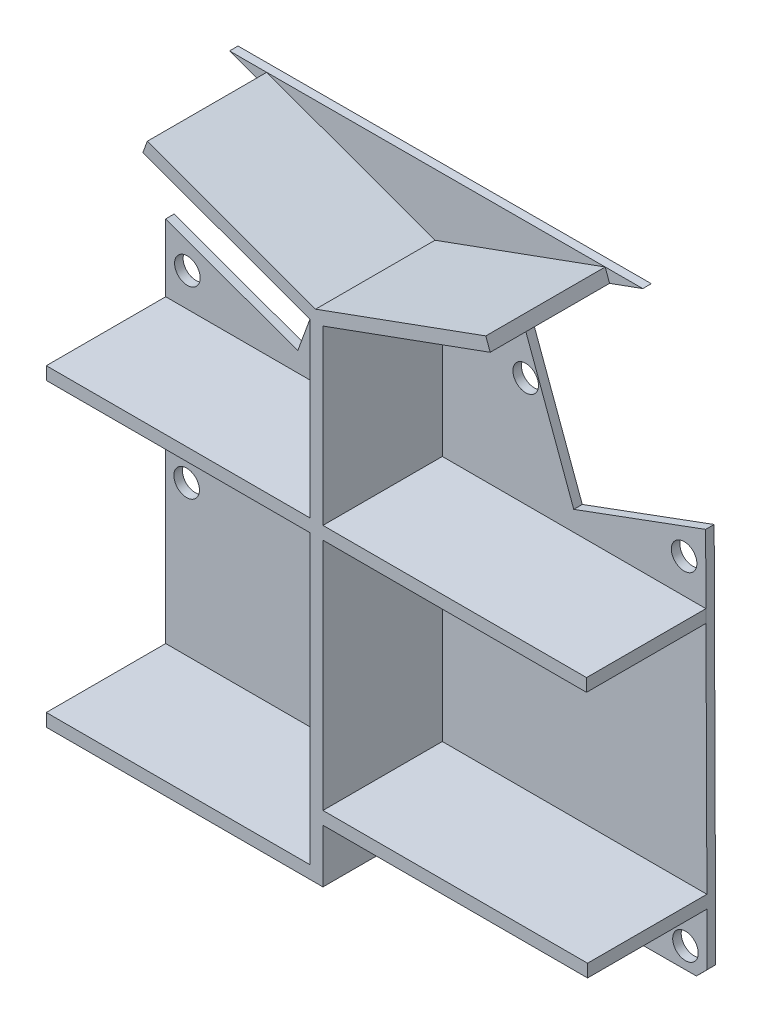
SolidWorks part; units mm, degrees
ref_plane "Front" through (0, 0, 0) normal (0, 0, 1) x (1, 0, 0)
ref_plane "Top" through (0, 0, 0) normal (0, 1, 0) x (1, 0, 0)
ref_plane "Right" through (0, 0, 0) normal (1, 0, 0) x (0, 0, -1)
sketch "20" plane through (0, 0, 0) normal (0, 0, 1) x (1, 0, 0)
  line L0 (1.27, 0) -> (62.23, 0)
  line L1 (63.5, 1.27) -> (63.5, 62.23)
  line L2 (62.23, 63.5) -> (58.039, 63.5)
  line L3 (37.846, 63.5) -> (25.4, 63.5)
  line L4 (5.207, 63.5) -> (1.27, 63.5)
  line L5 (0, 62.23) -> (0, 1.27)
  line L6 (5.969, 61.214) -> (20.32, 56.007)
  line L7 (20.32, 56.007) -> (25.4, 63.5)
  line L8 (5.969, 61.214) -> (5.207, 63.5)
  line L9 (57.277, 61.214) -> (42.926, 56.007)
  line L10 (42.926, 56.007) -> (37.846, 63.5)
  line L11 (57.277, 61.214) -> (58.039, 63.5)
  arc A0 (0, 1.27) -> (1.27, 0) centre (1.27, 1.27) ccw
  arc A1 (62.23, 0) -> (63.5, 1.27) centre (62.23, 1.27) ccw
  arc A2 (63.5, 62.23) -> (62.23, 63.5) centre (62.23, 62.23) ccw
  arc A3 (1.27, 63.5) -> (0, 62.23) centre (1.27, 62.23) ccw
  circle A4 centre (2.54, 2.54) radius 1.4986
  circle A5 centre (60.96, 20.32) radius 1.4986
  circle A6 centre (2.54, 41.91) radius 1.4986
  circle A7 centre (60.96, 41.91) radius 1.4986
  circle A8 centre (21.082, 50.8) radius 1.4986
  circle A9 centre (42.418, 50.8) radius 1.4986
  circle A10 centre (54.61, 3.81) radius 0.7
  circle A11 centre (54.61, 13.97) radius 0.7
  circle A12 centre (46.6997, 51.3854) radius 1.6256
  circle A13 centre (57.4403, 55.2946) radius 1.6256
  circle A14 centre (5.8057, 55.2946) radius 1.6256
  circle A15 centre (16.5463, 51.3854) radius 1.6256
sketch "22" plane through (0, 0, 0) normal (0, 0, 1) x (1, 0, 0)
  line L1 (48.6973, 40.5991) -> (62.8434, 45.7478)
  line L2 (58.121, 61.4079) -> (42.2487, 55.6309)
  line L3 (56.4815, 63.2271) -> (42.3353, 58.0783)
  line L4 (42.3353, 58.0783) -> (48.6973, 40.5991)
  line L5 (62.8434, 45.7478) -> (56.4815, 63.2271)
  line L6 (0.4026, 45.7478) -> (14.5488, 40.5991)
  line L7 (20.9973, 55.6309) -> (5.125, 61.4079)
  line L8 (20.9107, 58.0783) -> (6.7645, 63.2271)
  line L9 (6.7645, 63.2271) -> (0.4026, 45.7478)
  line L10 (14.5488, 40.5991) -> (20.9107, 58.0783)
  arc A2 (62.8608, 45.7001) -> (62.826, 45.7956) centre (62.8434, 45.7478) ccw
  arc A3 (48.6799, 40.6468) -> (48.7146, 40.5513) centre (48.6972, 40.599) ccw
  arc A4 (42.2313, 55.6786) -> (42.2661, 55.5831) centre (42.2487, 55.6309) ccw
  arc A5 (58.1384, 61.3602) -> (58.1037, 61.4557) centre (58.1211, 61.4079) ccw
  arc A6 (42.318, 58.126) -> (42.3527, 58.0306) centre (42.3353, 58.0783) ccw
  arc A7 (56.4988, 63.1793) -> (56.4641, 63.2748) centre (56.4815, 63.2271) ccw
  arc A8 (48.6495, 40.5817) -> (48.745, 40.6165) centre (48.6972, 40.5991) ccw
  arc A9 (42.3831, 58.0957) -> (42.2876, 58.0609) centre (42.3353, 58.0783) ccw
  arc A10 (56.5292, 63.2444) -> (56.4337, 63.2097) centre (56.4815, 63.2271) ccw
  arc A11 (62.7956, 45.7305) -> (62.8911, 45.7652) centre (62.8434, 45.7478) ccw
  arc A12 (14.5314, 40.5513) -> (14.5661, 40.6468) centre (14.5487, 40.599) ccw
  arc A13 (0.42, 45.7956) -> (0.3852, 45.7001) centre (0.4026, 45.7478) ccw
  arc A14 (5.1423, 61.4557) -> (5.1076, 61.3602) centre (5.1249, 61.4079) ccw
  arc A15 (20.9799, 55.5831) -> (21.0147, 55.6786) centre (20.9973, 55.6309) ccw
  arc A16 (6.7819, 63.2748) -> (6.7472, 63.1793) centre (6.7645, 63.2271) ccw
  arc A17 (20.8933, 58.0306) -> (20.928, 58.126) centre (20.9107, 58.0783) ccw
  arc A18 (0.3549, 45.7652) -> (0.4504, 45.7305) centre (0.4027, 45.7478) ccw
  arc A19 (6.8123, 63.2097) -> (6.7168, 63.2444) centre (6.7645, 63.2271) ccw
  arc A20 (20.9584, 58.0609) -> (20.8629, 58.0957) centre (20.9107, 58.0783) ccw
  arc A21 (14.501, 40.6165) -> (14.5965, 40.5817) centre (14.5488, 40.5991) ccw
sketch "Sketch9" plane through (0, 0, 0) normal (0, 0, 1) x (1, 0, 0)
  line L0 (31.623, 63.5) -> (31.75, 0) construction
  line L1 (37.846, 63.5) -> (25.4, 63.5) construction
  line L2 (1.27, 0) -> (62.23, 0) construction
  line L3 (0, 45.8943) -> (15.4885, 40.2571)
  line L4 (0.4026, 45.7478) -> (14.5488, 40.5991) construction
  line L5 (14.5488, 40.5991) -> (20.9107, 58.0783) construction
  line L6 (60.96, 20.32) -> (2.4587, 20.32) construction
  line L7 (15.4885, 40.2571) -> (21.1158, 55.7183)
  line L8 (21.1158, 55.7183) -> (31.6386, 55.7183)
  line L9 (5.969, 61.214) -> (20.32, 56.007) construction
  line L10 (0, 62.23) -> (0, 1.27) construction
  line L11 (0, 45.8943) -> (0, 1.27)
  line L12 (0, 1.27) -> (1.27, 0)
  line L13 (1.27, 0) -> (31.75, 0)
  line L14 (62.2298, 0.1219) -> (31.75, 0)
  line L15 (63.4947, 1.397) -> (62.2298, 0.1219)
  line L16 (63.3162, 46.021) -> (63.4947, 1.397)
  line L17 (63.3162, 46.021) -> (47.8503, 40.3218)
  line L18 (47.8503, 40.3218) -> (42.1612, 55.7604)
  line L19 (42.1612, 55.7604) -> (31.6386, 55.7183)
  line L20 (2.54, 2.54) -> (60.9498, 2.54) construction
  circle A0 centre (60.9498, 2.54) radius 1.4986
  circle A1 centre (21.082, 50.8) radius 1.4986
  circle A2 centre (2.54, 41.91) radius 1.4986
  circle A4 centre (2.54, 41.91) radius 1.4986 construction
  circle A5 centre (21.082, 50.8) radius 1.4986 construction
  circle A6 centre (2.54, 2.54) radius 1.4986 construction
  circle A7 centre (60.7921, 42.0265) radius 1.4986
  circle A8 centre (42.2147, 50.8423) radius 1.4986
  circle A10 centre (2.4587, 20.32) radius 1.4986
  circle A11 centre (60.96, 20.32) radius 1.4986 construction
  point P7 (31.6865, 31.75)
  point P41 (31.7449, 2.54)
  point P51 (31.7094, 20.32)
  dimension "D1" = 1
extrude "Boss-Extrude2" add sketch "Sketch9" along normal blind 1
sketch "Sketch13" plane through (0, 0, 0) normal (0, 0, -1) x (-1, 0, 0)
  line L0 (-21.1158, 55.7183) -> (-23.0473, 61.0252)
  line L1 (-23.0473, 61.0252) -> (-7.4808, 66.691)
  line L2 (-7.4808, 66.691) -> (-55.9471, 66.7879)
  line L3 (-55.9471, 66.7879) -> (-40.2085, 61.0596)
  line L4 (-40.2085, 61.0596) -> (-42.1612, 55.7604)
  line L5 (-21.1158, 55.7183) -> (-15.4885, 40.2571) construction
  line L7 (-21.1158, 55.7183) -> (-42.1612, 55.7604) construction
  line L8 (-47.8503, 40.3218) -> (-42.1612, 55.7604) construction
  line L9 (-20.9107, 58.0783) -> (-6.7645, 63.2271) construction
  line L10 (-56.4815, 63.2271) -> (-42.3353, 58.0783) construction
  line L12 (-21.1158, 55.7183) -> (-27.798, 50.0983)
  line L13 (-27.798, 50.0983) -> (-42.1612, 55.7604)
  dimension "D1" = 3.5
  dimension "D2" = 11
extrude "Boss-Extrude8" add sketch "Sketch13" against normal blind 1
sketch "Sketch11" plane through (0, 0, 1) normal (0, 0, 1) x (1, 0, 0)
  line L0 (32.4388, 58.2316) -> (32.4388, 9.04)
  line L2 (32.4388, 9.04) -> (63.4641, 9.04)
  line L3 (63.4947, 1.397) -> (63.3162, 46.021) construction
  line L4 (63.4641, 9.04) -> (63.4701, 7.54)
  line L5 (63.4701, 7.54) -> (32.4388, 7.54)
  line L6 (32.4388, 7.54) -> (32.4388, 1.27)
  line L8 (32.4388, 1.27) -> (0, 1.27)
  line L9 (0, 45.8943) -> (0, 1.27) construction
  line L10 (0, 1.27) -> (0, 2.77)
  line L11 (0, 2.77) -> (30.9409, 2.77)
  line L12 (30.9409, 2.77) -> (30.9409, 58.1522)
  line L14 (30.9409, 58.1522) -> (11.3295, 65.2902)
  line L15 (23.0473, 61.0252) -> (7.4808, 66.691) construction
  line L16 (11.3295, 65.2902) -> (11.8425, 66.6997)
  line L17 (7.4808, 66.691) -> (55.9471, 66.7879) construction
  line L18 (11.8425, 66.6997) -> (31.5808, 59.5156)
  line L19 (31.5808, 59.5156) -> (51.5371, 66.7791)
  line L20 (51.5371, 66.7791) -> (52.0501, 65.3696)
  line L21 (55.9471, 66.7879) -> (40.2085, 61.0596) construction
  line L22 (52.0501, 65.3696) -> (32.4388, 58.2316)
  line L23 (30.9409, 58.1522) -> (32.4388, 58.2316) construction
  circle A0 centre (60.9498, 2.54) radius 1.4986 construction
  point P0 (29.4005, 56.0524)
  dimension "D1" = 1.5
  dimension "D2" = 5
extrude "Boss-Extrude3" add sketch "Sketch11" along normal blind 14
sketch "Sketch12" plane through (0, 0, 1) normal (0, 0, 1) x (1, 0, 0)
  line L5 (63.4641, 9.04) -> (63.3162, 46.021) construction
  line L6 (63.3483, 37.9875) -> (0, 37.9875)
  line L7 (63.3483, 37.9875) -> (63.3483, 36.4875)
  line L8 (63.3483, 36.4875) -> (0, 36.4875)
  line L9 (0, 37.9875) -> (0, 36.4875)
  line L10 (0, 45.8943) -> (0, 2.77) construction
extrude "Boss-Extrude4" add sketch "Sketch12" along normal blind 14
